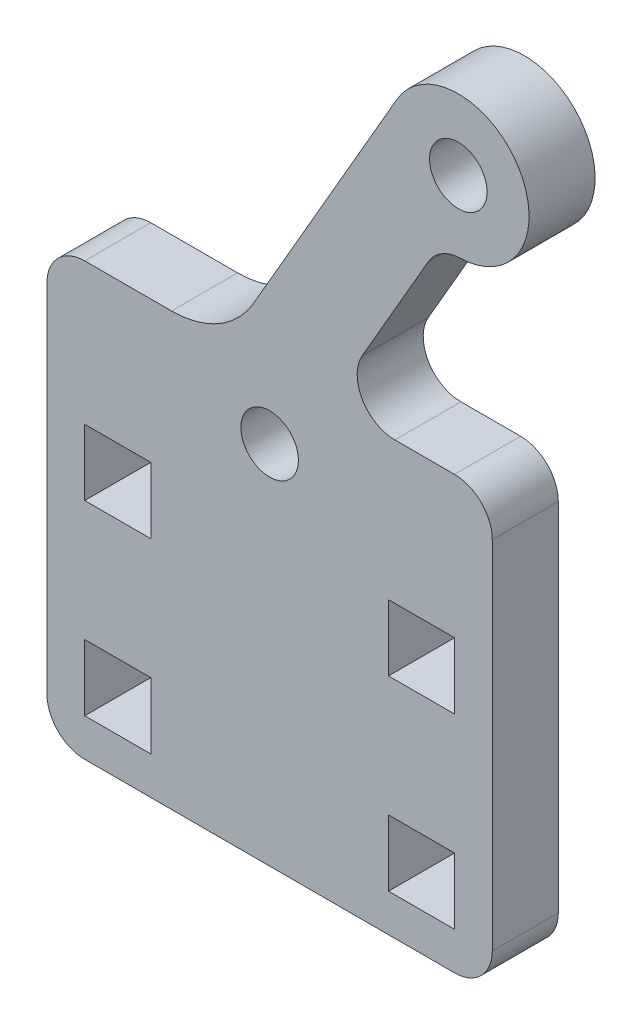
SolidWorks part; units mm, degrees
material "Balsa"
ref_plane "Front Plane" through (0, 0, 0) normal (0, 0, 1) x (1, 0, 0)
ref_plane "Top Plane" through (0, 0, 0) normal (0, 1, 0) x (1, 0, 0)
ref_plane "Right Plane" through (0, 0, 0) normal (1, 0, 0) x (0, 0, -1)
sketch "Sketch1" plane through (0, 0, 0) normal (0, 0, 1) x (1, 0, 0)
  line L0 (0, -6.9855) -> (0, 22.204) construction
  line L1 (-11.8, 0) -> (11.8, 0)
  line L2 (-11.8, 0) -> (-11.8, 22.88)
  line L3 (-11.8, 22.88) -> (-2.3094, 22.88)
  line L4 (11.8, 0) -> (11.8, 22.88)
  line L5 (-7.1026, 8.69) -> (6.6682, 8.69) construction
  line L6 (-9.8, 2) -> (-6.3, 2)
  line L7 (-9.8, 2) -> (-9.8, 5.5)
  line L8 (-9.8, 5.5) -> (-6.3, 5.5)
  line L9 (-6.3, 2) -> (-6.3, 5.5)
  line L10 (6.3, 2) -> (9.8, 2)
  line L11 (6.3, 2) -> (6.3, 5.5)
  line L12 (6.3, 5.5) -> (9.8, 5.5)
  line L13 (9.8, 2) -> (9.8, 5.5)
  line L14 (6.3, 15.38) -> (6.3, 11.88)
  line L15 (6.3, 11.88) -> (9.8, 11.88)
  line L16 (9.8, 15.38) -> (9.8, 11.88)
  line L17 (6.3, 15.38) -> (9.8, 15.38)
  line L18 (-9.8, 15.38) -> (-6.3, 15.38)
  line L19 (-9.8, 15.38) -> (-9.8, 11.88)
  line L20 (-9.8, 11.88) -> (-6.3, 11.88)
  line L21 (-6.3, 15.38) -> (-6.3, 11.88)
  line L22 (0, 19.38) -> (10, 36.7005) construction
  line L23 (9.0589, 33.0705) -> (3.1754, 22.88)
  line L24 (-2.3094, 22.88) -> (6.7524, 38.5755)
  line L25 (3.1754, 22.88) -> (11.8, 22.88)
  circle A0 centre (0, 19.38) radius 1.525
  circle A1 centre (10, 36.7005) radius 1.525
  arc A2 (9.0589, 33.0705) -> (6.7524, 38.5755) centre (10, 36.7005) ccw
  point P11 (0, 0)
  dimension "D8" = 3.05
  dimension "D14" = 7.5
  dimension "D1" = 23.6
  dimension "D2" = 22.88
  dimension "D3" = 2
  dimension "D4" = 2
  dimension "D5" = 3.5
  dimension "D6" = 2
  dimension "D7" = 3.19
  dimension "D9" = 20
  dimension "D10" = 10
  dimension "D11" = 4
  dimension "D12" = 1
extrude "Boss-Extrude1" add sketch "Sketch1" along normal blind 3.5
fillet "Fillet1" radius 2 4 edges at (-11.8, 0, 1.75) (-11.8, 22.88, 1.75) (11.8, 0, 1.75) (11.8, 22.88, 1.75)
fillet "Fillet2" radius 2 2 edges at (3.1754, 22.88, 1.75) (9.0589, 33.0705, 1.75)
fillet "Fillet3" radius 5 1 edges at (-2.3094, 22.88, 1.75)
